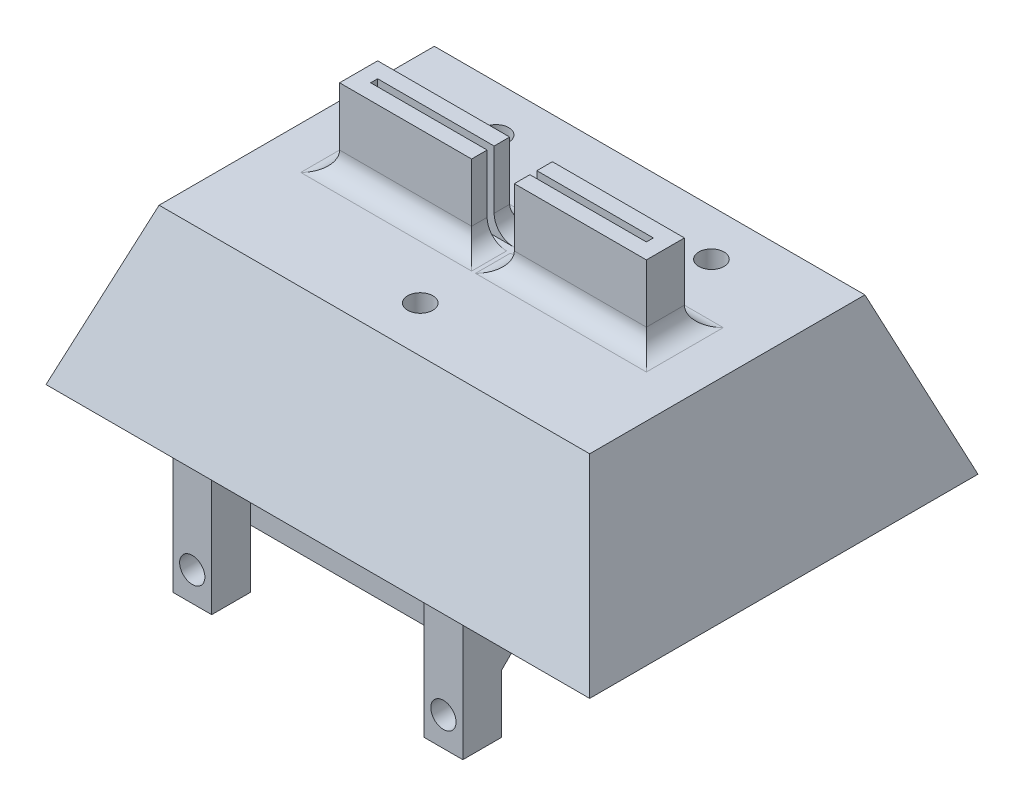
SolidWorks part; units mm, degrees
ref_plane "Front Plane" through (0, 0, 0) normal (0, 0, 1) x (1, 0, 0)
ref_plane "Top Plane" through (0, 0, 0) normal (0, 1, 0) x (1, 0, 0)
ref_plane "Right Plane" through (0, 0, 0) normal (1, 0, 0) x (0, 0, -1)
sketch "Sketch1" plane through (0, 0, 0) normal (0, 1, 0) x (1, 0, 0)
  line L1 (-70, -50) -> (70, -50)
  line L2 (-70, -50) -> (-70, 50)
  line L3 (-70, 50) -> (70, 50)
  line L4 (70, -50) -> (70, 50)
  line L5 (-70, -50) -> (70, 50) construction
  line L6 (-70, 50) -> (70, -50) construction
  point P0 (0, 0)
  point P6 (0, 0)
  dimension "D1" = 140
  dimension "D2" = 100
extrude "Boss-Extrude2" add sketch "Sketch1" along normal blind 40 draft 20
shell "Shell1" thickness 5
sketch "Sketch4" plane through (0, 0, 0) normal (0, -1, 0) x (1, 0, 0)
  line L0 (-64.6791, 44.6791) -> (64.6791, 44.6791) construction
  line L1 (0, 44.6791) -> (-64.6791, 44.6791) construction
  line L2 (-32.3396, 44.6791) -> (-32.3396, -44.6791) construction
  line L3 (64.6791, -44.6791) -> (-64.6791, -44.6791) construction
  line L4 (0, 44.6791) -> (0, -44.6791) construction
  line L5 (-27.3396, 44.6791) -> (-37.3396, 44.6791)
  line L6 (-37.3396, 44.6791) -> (-37.3396, -44.6791)
  line L7 (-27.3396, -44.6791) -> (-27.3396, 44.6791)
  line L8 (27.3396, -44.6791) -> (27.3396, 44.6791)
  line L9 (37.3396, 44.6791) -> (37.3396, -44.6791)
  line L10 (-32.3396, 44.6791) -> (0, 44.6791) construction
  line L11 (-16.1698, 44.6791) -> (-16.1698, -44.6791) construction
  line L12 (-5, -44.6791) -> (-5, 44.6791)
  line L13 (5, 44.6791) -> (5, -44.6791)
  point P13 (-32.3396, 44.6791)
  line M10 (-64.6791, 44.6791) -> (64.6791, 44.6791)
  line M12 (64.6791, -44.6791) -> (-64.6791, -44.6791)
  dimension "D1" = 10
extrude "Boss-Extrude3" add sketch "Sketch4" against normal up to body separate body contours L7 L6 M12 M10 | L9 L8 M10 M12 | L13 L12 M10 M12
sketch "Sketch8" plane through (0, 0, 0) normal (0, -1, 0) x (1, 0, 0)
  line L0 (-37.3396, 44.6791) -> (-37.3396, 50) construction
  line L1 (-70, 50) -> (70, 50) construction
  line L2 (0, 50) -> (0, -50) construction
  line L3 (-37.3396, 50) -> (-27.3396, 50)
  line L4 (-37.3396, 50) -> (-37.3396, 40)
  line L5 (-37.3396, 40) -> (-27.3396, 40)
  line L6 (-27.3396, 50) -> (-27.3396, 40)
  line L7 (70, -50) -> (-70, -50) construction
  line L8 (37.3396, 40) -> (27.3396, 40)
  line L9 (27.3396, 50) -> (27.3396, 40)
  line L10 (37.3396, 50) -> (27.3396, 50)
  line L11 (37.3396, 50) -> (37.3396, 40)
  dimension "D1" = 10
  dimension "D2" = 10
extrude "Boss-Extrude4" add sketch "Sketch8" along normal blind 30 separate body
sketch "Sketch9" plane through (37.3396, 0, 0) normal (1, 0, 0) x (0, 0, -1)
  line L0 (-40, -15) -> (-25, 0)
  line L1 (-40, -30) -> (-40, 0) construction
  line L3 (-40, -10) -> (-30, 0)
  line L4 (-50, 0) -> (50, 0) construction
  line L5 (-30, 0) -> (-25, 0)
  line L6 (-40, -10) -> (-40, -15)
  dimension "D1" = 45
  dimension "D2" = 5
  dimension "D3" = 5
extrude "Boss-Extrude5" add sketch "Sketch9" against normal up to surface (74.6791 mm away) up to face at (-37.3396, 17.5, 0)
sketch "Sketch12" plane through (0, 40, 0) normal (0, 1, 0) x (1, 0, 0)
  line L0 (35.5, 0) -> (-35.5, 0) construction
  line L1 (-35.5, -0.9) -> (-35.5, 0.9)
  line L2 (-35.5, 0.9) -> (-5.5, 0.9)
  line L3 (-35.5, -0.9) -> (-5.5, -0.9)
  line L4 (0, -35.4412) -> (0, 35.4412) construction
  line L5 (55.4412, 35.4412) -> (-55.4412, 35.4412) construction
  line L6 (-5.5, 0.9) -> (-5.5, 4.9)
  line L7 (-5.5, 4.9) -> (-33.4333, 4.9)
  line L8 (-5.5, -0.9) -> (-5.5, -4.9)
  line L9 (-5.5, -4.9) -> (-35.5, -4.9)
  line L10 (-33.4333, 4.9) -> (-39.5, 4.9)
  line L11 (-39.5, 4.9) -> (-39.5, -4.9)
  line L12 (-39.5, -4.9) -> (-35.5, -4.9)
  line L13 (39.5, 4.9) -> (39.5, -4.9)
  line L14 (33.4333, 4.9) -> (39.5, 4.9)
  line L15 (5.5, 4.9) -> (33.4333, 4.9)
  line L16 (5.5, 0.9) -> (5.5, 4.9)
  line L17 (35.5, 0.9) -> (5.5, 0.9)
  line L18 (35.5, -0.9) -> (35.5, 0.9)
  line L19 (35.5, -0.9) -> (5.5, -0.9)
  line L20 (5.5, -0.9) -> (5.5, -4.9)
  line L21 (5.5, -4.9) -> (35.5, -4.9)
  line L22 (39.5, -4.9) -> (35.5, -4.9)
  point P4 (0, 0)
  point P7 (-35.5, 0)
  point P14 (0, 0)
  dimension "D1" = 71
  dimension "D2" = 1.8
  dimension "D3" = 30
  dimension "D4" = 30
  dimension "D5" = 4
  dimension "D6" = 4
  dimension "D7" = 6.0667
  dimension "D8" = 4
extrude "Boss-Extrude6" add sketch "Sketch12" along normal blind 20
sketch "Sketch13" plane through (0, 0, 40) normal (0, 0, -1) x (-1, 0, 0)
  line L0 (-32.3396, -15) -> (-32.3396, -30) construction
  line L1 (-27.3396, -15) -> (-37.3396, -15) construction
  line L2 (-27.3396, -30) -> (-37.3396, -30) construction
  line L3 (-37.3396, -22.5) -> (-27.3396, -22.5) construction
  line L4 (-37.3396, -30) -> (-37.3396, -15) construction
  line L5 (-27.3396, -30) -> (-27.3396, -15) construction
  line L6 (0, -60) -> (0, 60) construction
  circle A0 centre (-32.3396, -22.5) radius 3.25
  circle A1 centre (32.3396, -22.5) radius 3.25
  point P18 (0, 0)
  dimension "D1" = 6.5
extrude "Cut-Extrude2" cut sketch "Sketch13" against normal through all
sketch "Sketch14" plane through (0, 40, 0) normal (0, 1, 0) x (1, 0, 0)
  line L0 (0, 35.4412) -> (0, -35.4412) construction
  line L1 (55.4412, 35.4412) -> (-55.4412, 35.4412) construction
  line L2 (-55.4412, -35.4412) -> (55.4412, -35.4412) construction
  line L3 (-55.4412, 35.4412) -> (-55.4412, -35.4412) construction
  line L4 (55.4412, -35.4412) -> (55.4412, 35.4412) construction
  circle A0 centre (0, -23.6312) radius 3.25
  circle A1 centre (27.7212, 23.6312) radius 3.25
  circle A2 centre (-27.7212, 23.6312) radius 3.25
  dimension "D1" = 6.5
  dimension "D5" = 6.5
  dimension "D6" = 6.5
  dimension "D2" = 11.81
  dimension "D3" = 11.81
  dimension "D4" = 11.81
  dimension "D7" = 27.72
  dimension "D8" = 27.72
extrude "Cut-Extrude3" cut sketch "Sketch14" against normal through all contours A2 | A1 | L0 A0
fillet "Fillet1" radius 5 10 edges at (5.5, 40, -2.9) (5.5, 40, 2.9) (-5.5, 40, 2.9) (-5.5, 40, -2.9) (22.5, 40, -4.9) (-22.5, 40, -4.9) (-39.5, 40, 0) (39.5, 40, 0) (22.5, 40, 4.9) (-22.5, 40, 4.9)
hole_wizard "CSK for M4 Countersunk Flat Head Screw1" positions "3DSketch1" profile "Sketch15" countersink size "M4" standard "ISO"
sketch3d "3DSketch1"
  point P0 (32.3396, -22.5, 40)
  point P5 (-32.3396, -22.5, 40)
sketch "Sketch15" plane through (32.3396, -22.5, 40) normal (1, 0, 0) x (0, 1, 0)
  line L0 (0, 0) -> (0, 11.3519)
  line L1 (0, 11.3519) -> (2.25, 10)
  line L2 (2.25, 10) -> (2.25, 2.45)
  line L3 (2.25, 2.45) -> (4.7, 0)
  line L5 (4.7, 0) -> (0, 0)
  line L6 (-2.25, 2.45) -> (-4.7, 0) construction
  line L10 (0, 11.3519) -> (-2.25, 10) construction
  line L11 (0, -6.35) -> (0, 107.95) construction
  dimension "Hole Dia." = 4.5
  dimension "Hole Depth" = 10
  dimension "Near C'Sink Dia." = 9.4
  dimension "Near C'Sink Angle" = 90
  dimension "Drill Angle" = 118
